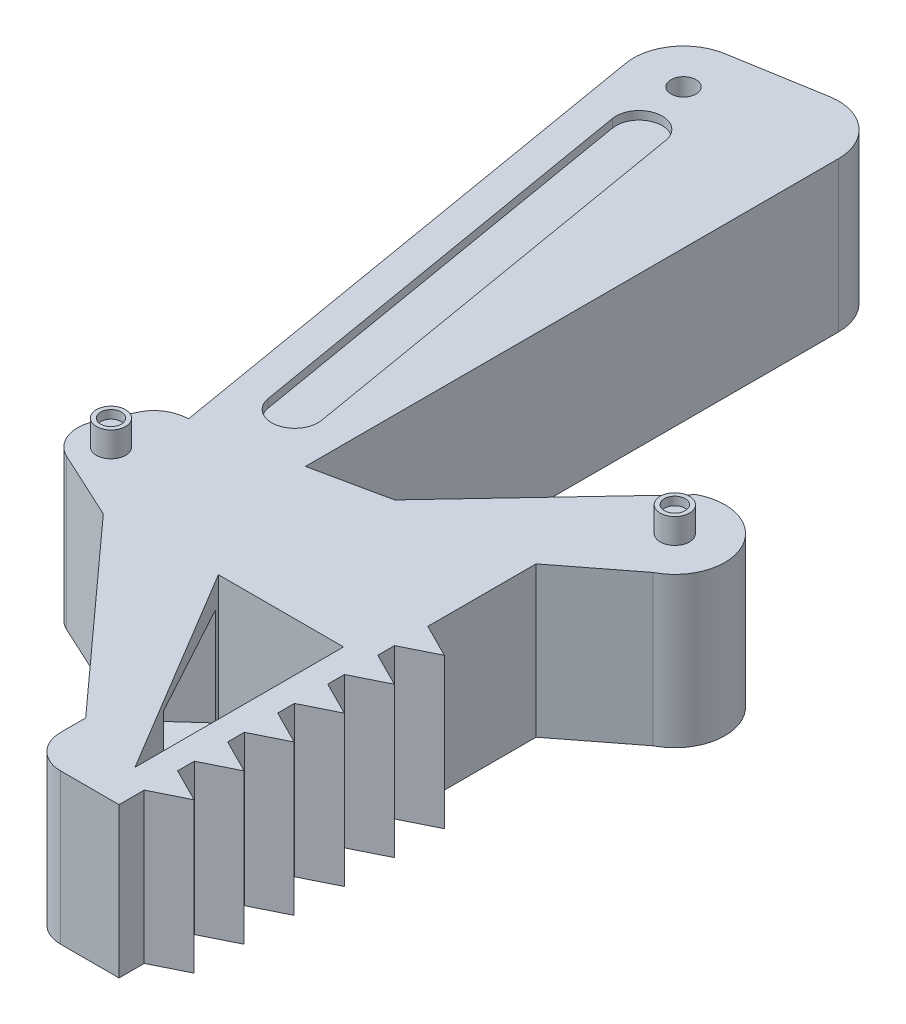
SolidWorks part; units mm, degrees
ref_plane "Front Plane" through (0, 0, 0) normal (0, 0, 1) x (1, 0, 0)
ref_plane "Top Plane" through (0, 0, 0) normal (0, 1, 0) x (1, 0, 0)
ref_plane "Right Plane" through (0, 0, 0) normal (1, 0, 0) x (0, 0, -1)
sketch "Sketch1" plane through (0, 0, 0) normal (0, 1, 0) x (1, 0, 0)
  line L0 (0, 0) -> (-59.8833, 0) construction
  line L1 (-12.9415, 0) -> (-36.6035, -4.0139)
  line L2 (-36.6035, -4.0139) -> (-24.8964, -73.0279)
  line L3 (-12.9415, 0) -> (-12.9415, -71)
  line L4 (-12.9415, -71) -> (-24.8964, -73.0279)
  line L5 (-24.8964, -73.0279) -> (-27.7303, -73.5087)
  line L6 (-27.7303, -73.5087) -> (-31.9284, -82.5848)
  line L7 (-31.9284, -82.5848) -> (-20.1294, -88.0423)
  line L8 (-20.1294, -88.0423) -> (0, -110.2866)
  line L9 (0, -110.2866) -> (0, -117.2866)
  line L10 (0, -117.2866) -> (11, -117.2866)
  line L11 (11, -117.2866) -> (11, -67.2866)
  line L12 (11, -67.2866) -> (18.908, -61.1658)
  line L13 (-12.9415, -71) -> (-4.1071, -69.1261)
  line L14 (-4.1071, -69.1261) -> (13.4322, -50.4879)
  arc A0 (13.4322, -50.4879) -> (18.908, -61.1658) centre (16.1701, -55.8268) cw
  dimension "D12" = 6
  dimension "D1" = 70
  dimension "D2" = 71
  dimension "D3" = 24
  dimension "D4" = 15
  dimension "D5" = 10
  dimension "D6" = 13
  dimension "D7" = 30
  dimension "D8" = 7
  dimension "D9" = 11
  dimension "D10" = 50
  dimension "D11" = 10
extrude "Boss-Extrude1" add sketch "Sketch1" along normal mid plane 18 contours A0 L14 L13 L4 L5 L6 L7 L8 L9 L10 L11 L12 | L4 L3 L1 L2
fillet "Fillet1" radius 6 2 edges at (-12.9415, 0, 0) (-36.6035, 0, 4.0139)
fillet "Fillet2" radius 4 3 edges at (0, 0, 117.2866) (-31.9284, 0, 82.5848) (-27.7303, 0, 73.5087)
sketch "Sketch2" plane through (0, 9, 0) normal (0, 1, 0) x (1, 0, 0)
  line L0 (11, -117.2866) -> (11, -112.2866) construction
  line L1 (11, -117.2866) -> (11, -67.2866) construction
  line L2 (11, -112.2866) -> (15, -112.2866) construction
  line L3 (15, -112.2866) -> (11, -114.2656)
  line L4 (11, -114.2656) -> (11, -110.2656)
  line L5 (11, -110.2656) -> (15, -112.2866)
  point P8 (0, 0)
  point P9 (0, 0)
  dimension "D1" = 5
  dimension "D2" = 4
  dimension "D3" = 4
extrude "Boss-Extrude2" add sketch "Sketch2" against normal blind 18
pattern_linear "LPattern1" count 6 spacing 6 along (0, 0, -1) of "Boss-Extrude2"
sketch "Sketch3" plane through (0, 9, 0) normal (0, 1, 0) x (1, 0, 0)
  line L0 (8.0829, -112.4576) -> (8.0829, -87.4576)
  line L1 (8.0829, -87.4576) -> (-6.9171, -87.4576)
  line L2 (-6.9171, -87.4576) -> (8.0829, -112.4576)
  dimension "D1" = 15
  dimension "D2" = 25
extrude "Cut-Extrude1" cut sketch "Sketch3" against normal blind 26
sketch "Sketch4" plane through (-54.8692, 0, 49.6526) normal (-0.7415, 0, 0.671) x (0.671, 0, 0.7415)
  line L0 (60.7748, 6) -> (60.7748, -6)
  line L4 (51.7748, 9) -> (51.7748, -9) construction
  line L5 (51.7748, 9) -> (51.7748, -9)
  line L6 (51.7748, 9) -> (81.7748, 9) construction
  line L8 (51.7748, 9) -> (81.7748, 9)
  line L9 (60.7748, 6) -> (78.9511, 8.0192)
  line L10 (78.9511, 8.0192) -> (78.9511, -8.0192)
  line L11 (78.9511, -8.0192) -> (60.7748, -6)
  point P2 (60.7748, 0)
  point P3 (78.9511, 0)
  point P8 (51.7748, 0)
  point P9 (69.8616, 9)
  dimension "D1" = 3
  dimension "D3" = 9
extrude "Cut-Extrude3" cut sketch "Sketch4" against normal blind 10
sketch "Sketch5" plane through (0, 9, 0) normal (0, 1, 0) x (1, 0, 0)
  circle A0 centre (-29.6846, -8.9259) radius 1.5
  dimension "D1" = 3
extrude "Cut-Extrude4" cut sketch "Sketch5" against normal through all
sketch "Sketch6" plane through (0, 9, 0) normal (0, 1, 0) x (1, 0, 0)
  circle A0 centre (-26.6187, -80.6336) radius 1.75
  circle A1 centre (16.1701, -55.8268) radius 1.75
  dimension "D1" = 3.5
  dimension "D2" = 3.5
extrude "Boss-Extrude3" add sketch "Sketch6" along normal blind 3
sketch "Sketch7" plane through (0, 12, 0) normal (0, 1, 0) x (1, 0, 0)
  circle A2 centre (-26.6187, -80.6336) radius 1.25
  circle A3 centre (-26.6187, -80.6336) radius 1.25
  dimension "D1" = 0.5
extrude "Cut-Extrude6" cut sketch "Sketch7" against normal blind 1
sketch "Sketch8" plane through (0, 12, 0) normal (0, 1, 0) x (1, 0, 0)
  circle A2 centre (16.1701, -55.8268) radius 1.25
  circle A3 centre (16.1701, -55.8268) radius 1.25
  dimension "D1" = 0.5
extrude "Cut-Extrude7" cut sketch "Sketch8" against normal blind 1
sketch "Sketch9" plane through (0, 9, 0) normal (0, 1, 0) x (1, 0, 0)
  line L0 (-27.9308, -16.0041) -> (-19.492, -65.7159) construction
  line L1 (-25.1962, -15.5399) -> (-16.7575, -65.2517)
  line L2 (-30.6654, -16.4683) -> (-22.2266, -66.1801)
  arc A0 (-25.1962, -15.5399) -> (-30.6654, -16.4683) centre (-27.9308, -16.0041) ccw
  arc A1 (-22.2266, -66.1801) -> (-16.7575, -65.2517) centre (-19.492, -65.7159) ccw
  point P2 (-23.7114, -40.86)
extrude "Cut-Extrude8" cut sketch "Sketch9" against normal blind 1 contours L2 A1 L1 A0
mirror "Mirror1" about plane through (0, 0, 0) normal (0, 1, 0) of "Cut-Extrude8", "Boss-Extrude3"
